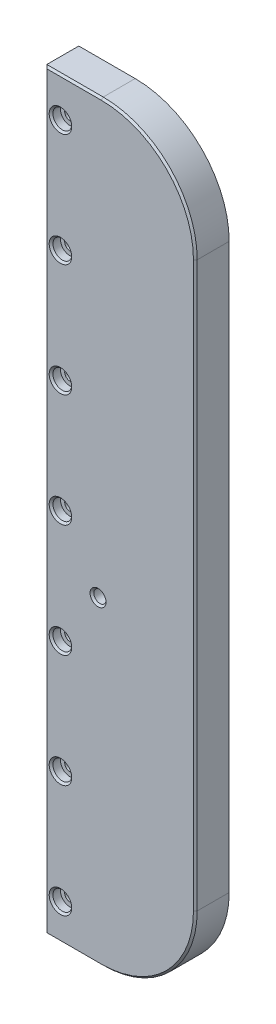
SolidWorks part; units mm, degrees
ref_plane "Front Plane" through (0, 0, 0) normal (0, 0, 1) x (1, 0, 0)
ref_plane "Top Plane" through (0, 0, 0) normal (0, 1, 0) x (1, 0, 0)
ref_plane "Right Plane" through (0, 0, 0) normal (1, 0, 0) x (0, 0, -1)
sketch "Sketch1" plane through (0, 0, 0) normal (0, 0, 1) x (1, 0, 0)
  line L1 (1, 271) -> (81, 271)
  line L2 (1, 271) -> (1, -129)
  line L3 (1, -129) -> (81, -129)
  line L4 (81, 271) -> (81, -129)
  dimension "D1" = 400
  dimension "D2" = 80
extrude "Boss-Extrude1" add sketch "Sketch1" along normal blind 18
fillet "Fillet1" radius 50 2 edges at (81, 271, 9) (81, -129, 9)
sketch "Sketch2" plane through (0, 0, 18) normal (0, 0, 1) x (1, 0, 0)
  circle A0 centre (9.25, -110) radius 2.5
  circle A1 centre (9.25, -50) radius 2.5
  circle A2 centre (9.25, 10) radius 2.5
  circle A3 centre (9.25, 70) radius 2.5
  circle A4 centre (9.25, 130) radius 2.5
  circle A5 centre (9.25, 190) radius 2.5
  circle A6 centre (9.25, 250) radius 2.5
  point P0 (0, -140)
  dimension "D1" = 7
hole_wizard "CBORE for M5 SHCS1" positions "Sketch3" profile "Sketch4" counterbore size "M5" standard "ANSI Metric"
sketch "Sketch3" plane through (0, 0, 18) normal (0, 0, 1) x (1, 0, 0)
  point P0 (9.25, 190)
  point P3 (9.25, 130)
  point P6 (9.25, 70)
  point P9 (9.25, 10)
  point P12 (9.25, -50)
  point P15 (9.25, -110)
  point P18 (9.25, 250)
sketch "Sketch4" plane through (9.25, 190, 18) normal (1, 0, 0) x (0, -1, 0)
  line L0 (0, 0) -> (0, 30)
  line L1 (0, 30) -> (2.75, 28.3476)
  line L2 (2.75, 28.3476) -> (2.75, 5)
  line L3 (2.75, 5) -> (5, 5)
  line L4 (5, 5) -> (5, 0)
  line L5 (5, 0) -> (0, 0)
  line L10 (0, 30) -> (-2.75, 28.3476) construction
  line L11 (0, -6.35) -> (0, 107.95) construction
  dimension "Hole Dia." = 5.5
  dimension "Hole Depth" = 30
  dimension "C'Bore Dia." = 10
  dimension "C'Bore Depth" = 5
  dimension "Drill Angle" = 118
chamfer "Chamfer1" distance 1 angle 45 13 edges at (66.3553, -114.3553, 18) (16, -129, 18) (1, 71, 18) (16, 271, 18) (66.3553, 256.3553, 18) (81, 71, 18) (14.25, -110, 18) (14.25, -50, 18) (14.25, 10, 18) (14.25, 70, 18) (14.25, 130, 18) (14.25, 190, 18) (14.25, 250, 18)
sketch "Sketch5" plane through (0, 0, 18) normal (0, 0, 1) x (1, 0, 0)
  circle A0 centre (29.25, 40) radius 3.25
extrude "Cut-Extrude1" cut sketch "Sketch5" against normal through all
chamfer "Chamfer2" distance 1 angle 45 2 edges at (32.5, 40, 0) (32.5, 40, 18)
